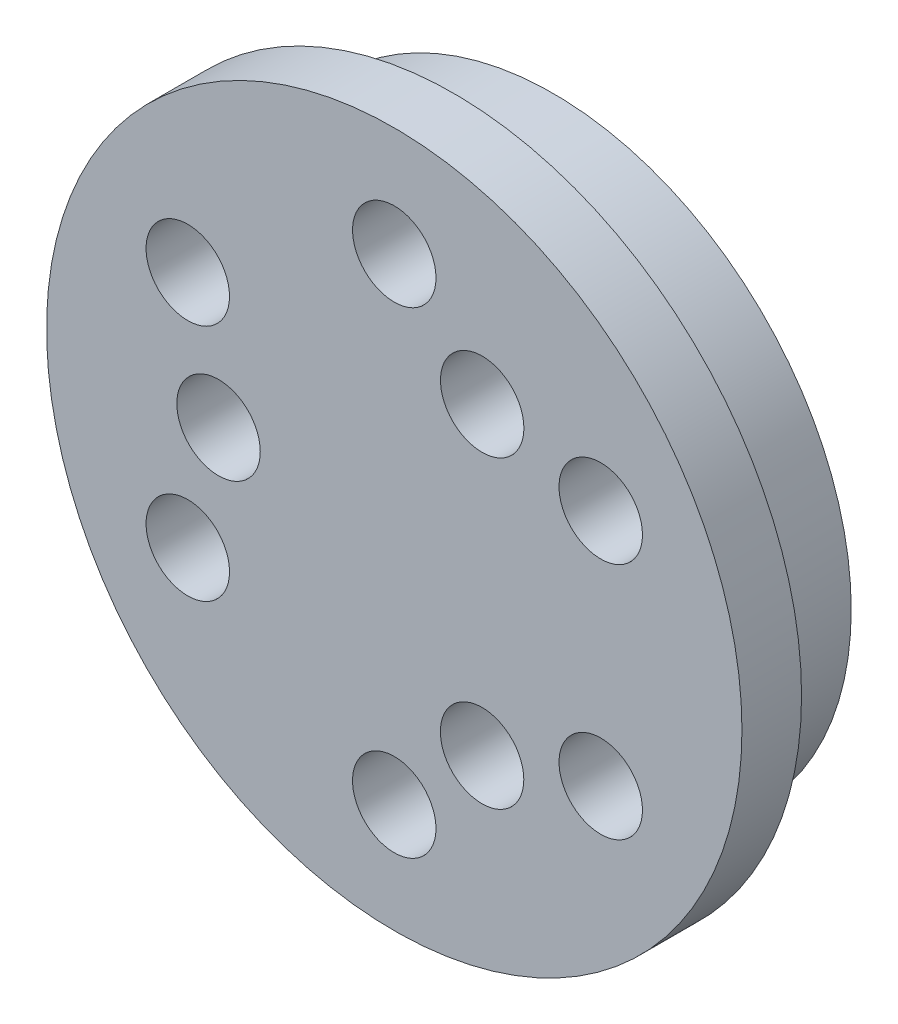
SolidWorks part; units mm, degrees
material "petg"
ref_plane "前视基准面" through (0, 0, 0) normal (0, 0, 1) x (1, 0, 0)
ref_plane "上视基准面" through (0, 0, 0) normal (0, 1, 0) x (1, 0, 0)
ref_plane "右视基准面" through (0, 0, 0) normal (1, 0, 0) x (0, 0, -1)
other "Configuration Table"
sketch "草图1" plane through (0, 0, 0) normal (0, 0, 1) x (1, 0, 0)
  line L0 (0, 0) -> (21.3337, 0) construction
  line L1 (0, 0) -> (14.317, 24.7977) construction
  circle A0 centre (0, 0) radius 15
  circle A1 centre (0, 0) radius 12 construction
  circle A2 centre (0, 12) radius 2.1
  circle A3 centre (10.3923, 6) radius 2.1
  circle A4 centre (10.3923, -6) radius 2.1
  circle A5 centre (0, -12) radius 2.1
  circle A6 centre (-10.3923, -6) radius 2.1
  circle A7 centre (-10.3923, 6) radius 2.1
  circle A8 centre (0, 0) radius 8.85 construction
  circle A9 centre (4.425, 7.6643) radius 2.1
  circle A10 centre (4.4197, -7.6551) radius 2.1
  circle A11 centre (-8.8447, 0.0092) radius 2.1
  point P18 (0, 0)
  point P29 (0, 0.0061)
  dimension "D1" = 30
  dimension "D2" = 24
  dimension "D3" = 6
  dimension "D4" = 17.7
  dimension "D6" = 3
  dimension "D7" = 8.85
  dimension "D8" = 4.2
  dimension "D9" = 4.2
  dimension "D5" = 60
extrude "凸台-拉伸1" add sketch "草图1" along normal blind 7
sketch "草图2" plane through (0, 0, 7) normal (0, 0, 1) x (1, 0, 0)
  circle A0 centre (-8.8447, 0.0092) radius 2.1 construction
  circle A2 centre (0, 0) radius 17.5
  circle A3 centre (-10.3923, -6) radius 2.1 construction
  circle A4 centre (0, -12) radius 2.1 construction
  circle A5 centre (4.4197, -7.6551) radius 2.1 construction
  circle A6 centre (10.3923, -6) radius 2.1 construction
  circle A7 centre (-8.8447, 0.0092) radius 2.1
  circle A8 centre (-10.3923, -6) radius 2.1
  circle A9 centre (0, -12) radius 2.1
  circle A10 centre (4.4197, -7.6551) radius 2.1
  circle A11 centre (10.3923, -6) radius 2.1
  circle A12 centre (10.3923, 6) radius 2.1 construction
  circle A13 centre (4.425, 7.6643) radius 2.1 construction
  circle A14 centre (0, 12) radius 2.1 construction
  circle A15 centre (-10.3923, 6) radius 2.1 construction
  circle A16 centre (10.3923, 6) radius 2.1
  circle A17 centre (4.425, 7.6643) radius 2.1
  circle A18 centre (0, 12) radius 2.1
  circle A19 centre (-10.3923, 6) radius 2.1
  dimension "D1" = 35
extrude "凸台-拉伸2" add sketch "草图2" against normal blind 2
sketch "草图3" plane through (0, 0, 7) normal (0, 0, 1) x (1, 0, 0)
  circle A0 centre (0, -12) radius 2.1 construction
  circle A1 centre (-10.3923, -6) radius 2.1 construction
  circle A2 centre (-8.8447, 0.0092) radius 2.1 construction
  circle A3 centre (-10.3923, 6) radius 2.1 construction
  circle A4 centre (0, 0) radius 17.5 construction
  circle A5 centre (0, -12) radius 2.1
  circle A6 centre (-10.3923, -6) radius 2.1
  circle A7 centre (-8.8447, 0.0092) radius 2.1
  circle A8 centre (-10.3923, 6) radius 2.1
  circle A9 centre (0, 0) radius 17.5
  circle A10 centre (4.4197, -7.6551) radius 2.1 construction
  circle A11 centre (10.3923, -6) radius 2.1 construction
  circle A12 centre (10.3923, 6) radius 2.1 construction
  circle A13 centre (4.425, 7.6643) radius 2.1 construction
  circle A14 centre (0, 12) radius 2.1 construction
  circle A15 centre (4.4197, -7.6551) radius 2.1
  circle A16 centre (10.3923, -6) radius 2.1
  circle A17 centre (10.3923, 6) radius 2.1
  circle A18 centre (4.425, 7.6643) radius 2.1
  circle A19 centre (0, 12) radius 2.1
sketch "草图5" plane through (0, 0, 7) normal (0, 0, 1) x (1, 0, 0)
  circle A0 centre (-10.3923, -6) radius 2.1 construction
  circle A1 centre (0, -12) radius 2.1 construction
  circle A2 centre (4.4197, -7.6551) radius 2.1 construction
  circle A3 centre (10.3923, -6) radius 2.1 construction
  circle A4 centre (10.3923, 6) radius 2.1 construction
  circle A5 centre (4.425, 7.6643) radius 2.1 construction
  circle A6 centre (0, 12) radius 2.1 construction
  circle A7 centre (-8.8447, 0.0092) radius 2.1 construction
  circle A8 centre (-10.3923, 6) radius 2.1 construction
  circle A9 centre (-10.3923, -6) radius 2.1
  circle A10 centre (0, -12) radius 2.1
  circle A11 centre (4.4197, -7.6551) radius 2.1
  circle A12 centre (10.3923, -6) radius 2.1
  circle A13 centre (10.3923, 6) radius 2.1
  circle A14 centre (4.425, 7.6643) radius 2.1
  circle A15 centre (0, 12) radius 2.1
  circle A16 centre (-8.8447, 0.0092) radius 2.1
  circle A17 centre (-10.3923, 6) radius 2.1
  circle A19 centre (0, 0) radius 17.5
  circle A20 centre (0, 0) radius 17.5
  dimension "D1" = 0
extrude "凸台-拉伸4" add sketch "草图5" along normal blind 1
